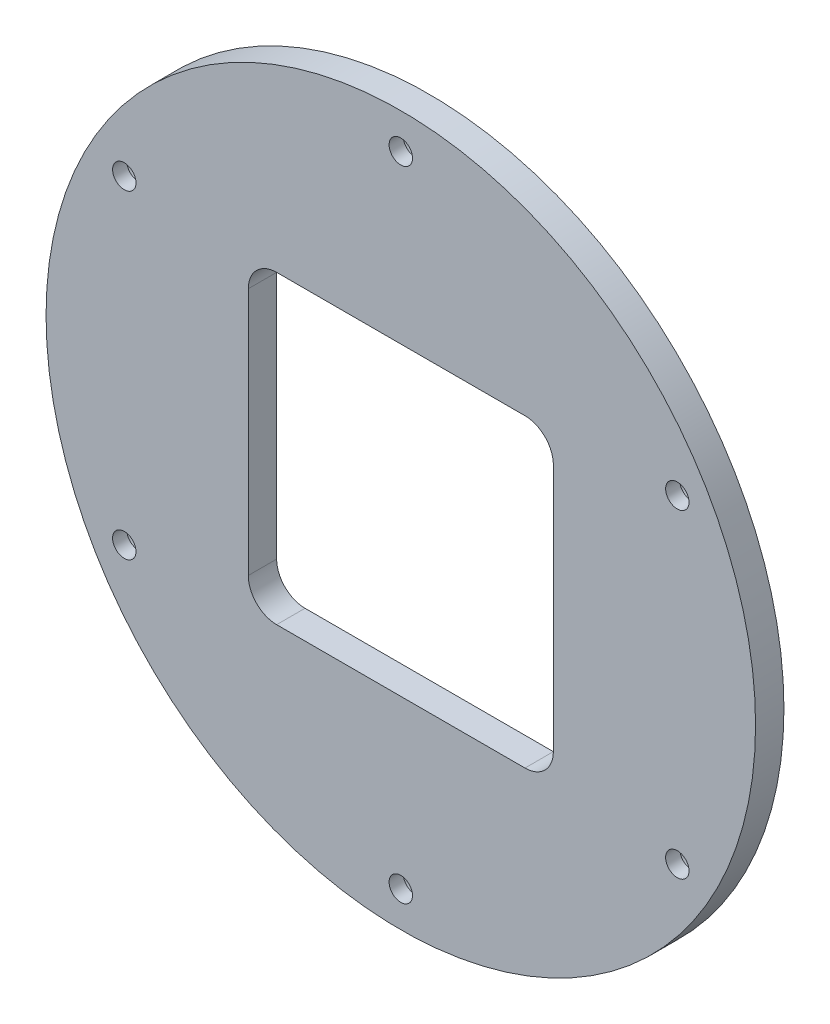
SolidWorks part; units mm, degrees
ref_plane "前视基准面" through (0, 0, 0) normal (0, 0, 1) x (1, 0, 0)
ref_plane "上视基准面" through (0, 0, 0) normal (0, 1, 0) x (1, 0, 0)
ref_plane "右视基准面" through (0, 0, 0) normal (1, 0, 0) x (0, 0, -1)
other "Configuration Table"
sketch "草图1" plane through (0, 0, 0) normal (0, 0, 1) x (1, 0, 0)
  line L0 (0, 0) -> (61.0193, 0) construction
  line L1 (0, 40) -> (0, -27.3482) construction
  line L2 (-38.9711, 22.5) -> (0, 0) construction
  line L4 (-21.5, -21.5) -> (21.5, -21.5)
  line L5 (-21.5, -21.5) -> (-21.5, 21.5)
  line L6 (-21.5, 21.5) -> (21.5, 21.5)
  line L7 (21.5, -21.5) -> (21.5, 21.5)
  circle A0 centre (0, 0) radius 50
  circle A6 centre (-38.9711, 22.5) radius 1.65
  circle A12 centre (0, 45) radius 1.65
  circle A13 centre (38.9711, 22.5) radius 1.65
  circle A14 centre (38.9711, -22.5) radius 1.65
  circle A15 centre (0, -45) radius 1.65
  circle A16 centre (-38.9711, -22.5) radius 1.65
  point P18 (0, 0)
  point P31 (0, 0)
  point P32 (0, 0)
  dimension "D1" = 100
  dimension "D6" = 3.3
  dimension "D7" = 45
  dimension "D8" = 60
  dimension "D10" = 43
  dimension "D11" = 43
  dimension "D9" = 6
extrude "凸台-拉伸1" add sketch "草图1" along normal blind 4
sketch "草图2" plane through (0, 0, 0) normal (0, 0, 1) x (1, 0, 0)
  circle A0 centre (0, 45) radius 3.15
  circle A1 centre (38.9711, 22.5) radius 3.15
  circle A2 centre (38.9711, -22.5) radius 3.15
  circle A3 centre (0, -45) radius 3.15
  circle A4 centre (-38.9711, -22.5) radius 3.15
  circle A5 centre (-38.9711, 22.5) radius 3.15
  point P15 (0, 0)
  dimension "D1" = 6.3
  dimension "D2" = 6
extrude "切除-拉伸1" cut sketch "草图2" along normal blind 2
fillet "圆角1" radius 4 4 edges at (-21.5, -21.5, 2) (21.5, -21.5, 2) (21.5, 21.5, 2) (-21.5, 21.5, 2)
